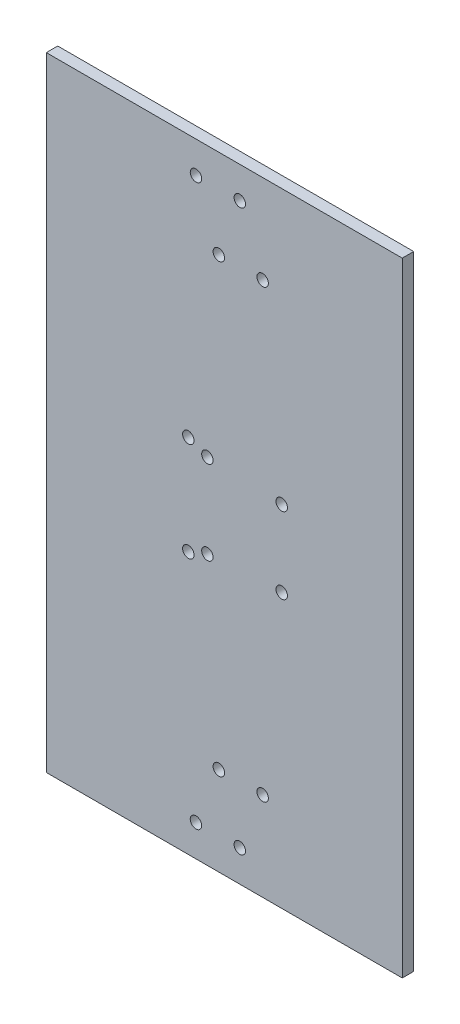
SolidWorks part; units mm, degrees
ref_plane "Płaszczyzna przednia" through (0, 0, 0) normal (0, 0, 1) x (1, 0, 0)
ref_plane "Płaszczyzna górna" through (0, 0, 0) normal (0, 1, 0) x (1, 0, 0)
ref_plane "Płaszczyzna prawa" through (0, 0, 0) normal (1, 0, 0) x (0, 0, -1)
sketch "Szkic1" plane through (0, 0, 0) normal (0, 0, 1) x (1, 0, 0)
  line L0 (-1, 16.3341) -> (-1, 9.5) construction
  line L1 (18.5, 11.7709) -> (18.5, 8.5) construction
  line L2 (2, 65.8704) -> (2, 57) construction
  line L3 (-4, 73.5) -> (28.4498, 73.5) construction
  line L4 (2, 58.5) -> (20.4279, 58.5) construction
  line L5 (0, 0) -> (63.3107, 0) construction
  line L7 (-43.2642, 0) -> (50.1299, 0)
  line L8 (-43.2642, 0) -> (-43.2642, 81.7904)
  line L9 (-43.2642, 81.7904) -> (50.1299, 81.7904)
  line L10 (50.1299, 0) -> (50.1299, 81.7904)
  circle A0 centre (-1, 11) radius 1.5
  circle A2 centre (18.5, 10) radius 1.5
  circle A4 centre (-6, 13) radius 1.5
  circle A6 centre (2, 58.5) radius 1.5
  circle A9 centre (13.5, 58.5) radius 1.5
  circle A10 centre (-4, 73.5) radius 1.5
  circle A11 centre (7.5, 73.5) radius 1.5
  point P25 (0, 0)
  dimension "D1" = 3
  dimension "D4" = 3
  dimension "D7" = 3
  dimension "D8" = 73.5
  dimension "D10" = 3
  dimension "D15" = 58.5
  dimension "D21" = 11.5
  dimension "D13" = 3
  dimension "D2" = 11
  dimension "D3" = 1
  dimension "D5" = 19.5
  dimension "D6" = 10
  dimension "D9" = 3
  dimension "D11" = 5
  dimension "D12" = 2
  dimension "D14" = 11.5
  dimension "D16" = 3
extrude "Dodanie-wyciągnięcie2" add sketch "Szkic1" along normal blind 3 contours A2 | A11 | A4 | A0 | L10 L9 L8 L7 | A9 | A6 | A10
mirror "Lustro4" about plane through (0, 0, 0) normal (0, 1, 0) of "Dodanie-wyciągnięcie2"
